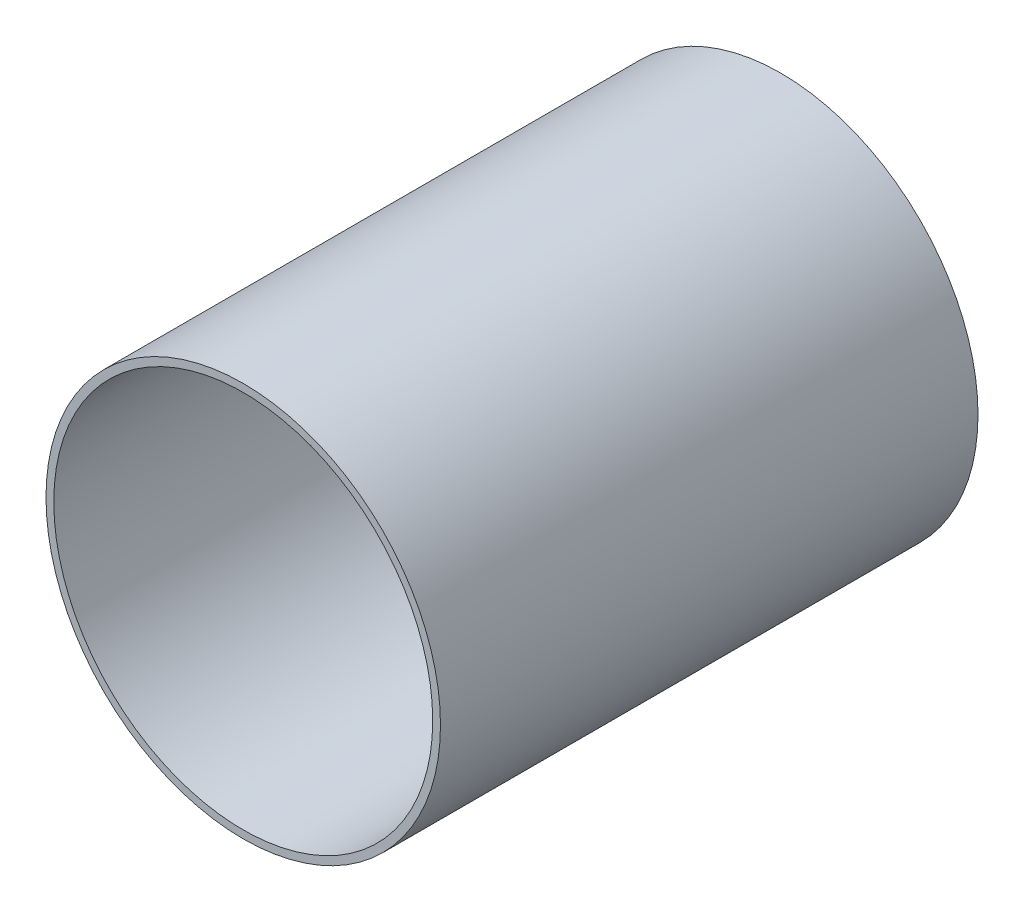
SolidWorks part; units mm, degrees
ref_plane "Plane1" through (0, 0, 0) normal (0, 0, 1) x (1, 0, 0)
ref_plane "Plane2" through (0, 0, 0) normal (0, 1, 0) x (1, 0, 0)
ref_plane "Plane3" through (0, 0, 0) normal (1, 0, 0) x (0, 0, -1)
sketch "Sketch1" plane through (0, 0, 0) normal (0, 0, 1) x (1, 0, 0)
  circle A0 centre (0, 0) radius 21.325
  circle A1 centre (0, 0) radius 22.2
extrude "BasePipe" add sketch "Sketch1" along normal mid plane 60.5
sketch3d "Трехмерный эскиз2" plane through (0, 0, 0) normal (0, 0, 1) x (1, 0, 0)
